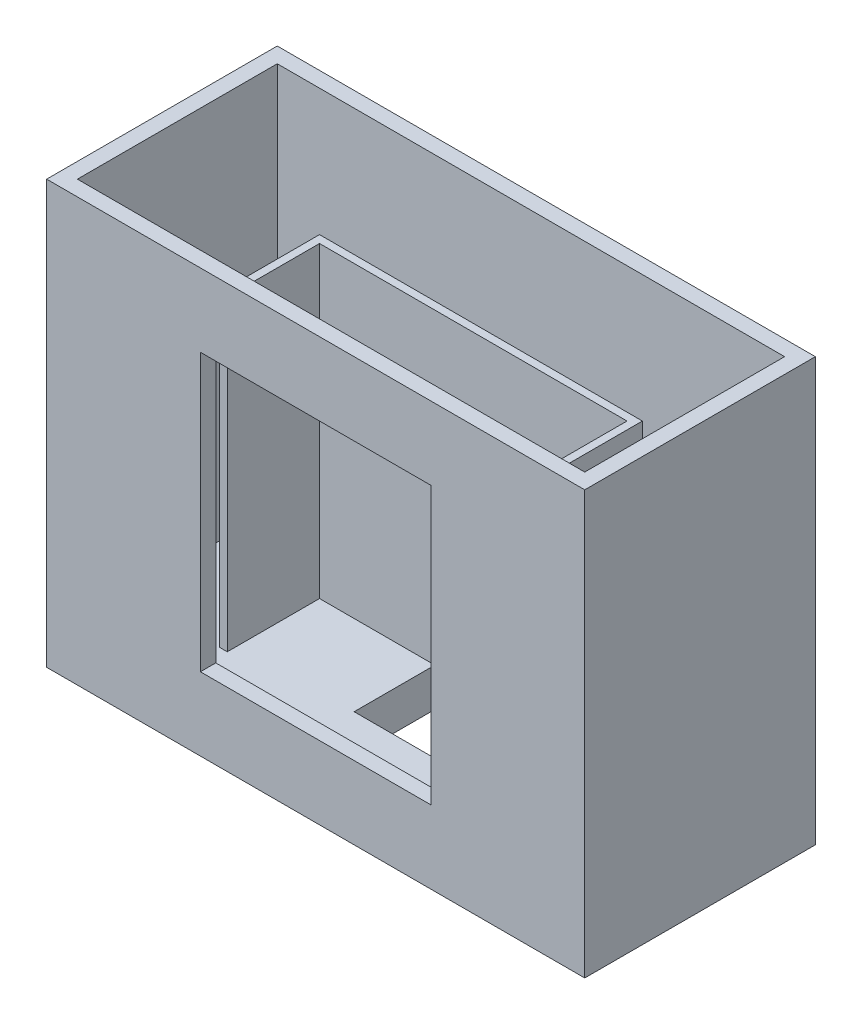
SolidWorks part; units mm, degrees
ref_plane "Front Plane" through (0, 0, 0) normal (0, 0, 1) x (1, 0, 0)
ref_plane "Top Plane" through (0, 0, 0) normal (0, 1, 0) x (1, 0, 0)
ref_plane "Right Plane" through (0, 0, 0) normal (1, 0, 0) x (0, 0, -1)
sketch "Sketch1" plane through (0, 0, 0) normal (0, 1, 0) x (1, 0, 0)
  line L1 (-35, 15) -> (35, 15)
  line L2 (-35, 15) -> (-35, -15)
  line L3 (-35, -15) -> (35, -15)
  line L4 (35, 15) -> (35, -15)
  line L5 (-35, 15) -> (35, -15) construction
  line L6 (-35, -15) -> (35, 15) construction
  point P0 (0, 0)
  dimension "D1" = 30
  dimension "D2" = 70
extrude "Boss-Extrude1" add sketch "Sketch1" along normal blind 5
sketch "Sketch2" plane through (0, 5, 0) normal (0, 1, 0) x (1, 0, 0)
  line L0 (35, -15) -> (35, 15) construction
  line L1 (-35, -15) -> (35, -15)
  line L2 (-35, -15) -> (-35, -13)
  line L3 (-35, -13) -> (35, -13)
  line L4 (35, -15) -> (35, -13)
  line L19 (-35, 15) -> (35, 15)
  line L20 (-35, 15) -> (-35, 13)
  line L21 (-35, 13) -> (35, 13)
  line L22 (35, 15) -> (35, 13)
  dimension "D1" = 2
  dimension "D2" = 2
extrude "Boss-Extrude2" add sketch "Sketch2" along normal blind 50
sketch "Sketch3" plane through (0, 5, 0) normal (0, 1, 0) x (1, 0, 0)
  line L0 (35, -13) -> (-35, -13) construction
  line L1 (-35, 13) -> (-33, 13)
  line L2 (-35, 13) -> (-35, -13)
  line L3 (-35, -13) -> (-33, -13)
  line L4 (-33, 13) -> (-33, -13)
  line L5 (35, -13) -> (-35, -13) construction
  line L6 (35, 13) -> (33, 13)
  line L7 (35, 13) -> (35, -13)
  line L8 (35, -13) -> (33, -13)
  line L9 (33, 13) -> (33, -13)
  dimension "D1" = 2
  dimension "D2" = 2
extrude "Boss-Extrude3" add sketch "Sketch3" along normal blind 50
sketch "Sketch4" plane through (0, 5, 0) normal (0, 1, 0) x (1, 0, 0)
  line L1 (-20, -5.5) -> (20, -5.5)
  line L2 (-20, -5.5) -> (-20, 5.5)
  line L3 (-20, 5.5) -> (20, 5.5)
  line L4 (20, -5.5) -> (20, 5.5)
  line L5 (-20, -5.5) -> (20, 5.5) construction
  line L6 (-20, 5.5) -> (20, -5.5) construction
  line L7 (-21, -6.5) -> (21, -6.5)
  line L8 (-21, -6.5) -> (-21, 6.5)
  line L9 (-21, 6.5) -> (21, 6.5)
  line L10 (21, -6.5) -> (21, 6.5)
  line L11 (-21, -6.5) -> (21, 6.5) construction
  line L12 (-21, 6.5) -> (21, -6.5) construction
  point P0 (0, 0)
  point P6 (0, 0)
  dimension "D1" = 40
  dimension "D2" = 11
  dimension "D3" = 13
  dimension "D4" = 42
extrude "Boss-Extrude4" add sketch "Sketch4" along normal blind 40
sketch "Sketch6" plane through (0, 0, 6.5) normal (0, 0, 1) x (1, 0, 0)
  line L5 (-21, 45) -> (21, 45) construction
  line L8 (-21, 5) -> (21, 5) construction
  line L14 (-20, 45) -> (20, 45)
  line L15 (-20, 45) -> (-20, 5)
  line L16 (-20, 5) -> (20, 5)
  line L17 (20, 45) -> (20, 5)
extrude "Cut-Extrude1" cut sketch "Sketch6" against normal blind 2
sketch "Sketch7" plane through (0, 0, 15) normal (0, 0, 1) x (1, 0, 0)
  line L0 (-35, 27.5) -> (35, 27.5)
  line L1 (-35, 55) -> (-35, 0) construction
  line L2 (35, 55) -> (35, 0) construction
  line L3 (0, 0) -> (0, 55)
  line L4 (-35, 55) -> (35, 55) construction
  line L6 (-15, 9.5) -> (15, 9.5)
  line L7 (-15, 9.5) -> (-15, 45.5)
  line L8 (-15, 45.5) -> (15, 45.5)
  line L9 (15, 9.5) -> (15, 45.5)
  line L10 (-15, 9.5) -> (15, 45.5) construction
  line L11 (-15, 45.5) -> (15, 9.5) construction
  point P11 (0, 27.5)
  dimension "D1" = 36
  dimension "D2" = 30
extrude "Cut-Extrude2" cut sketch "Sketch7" against normal blind 5 contours L8 L7 L0 L3 | L0 L9 L8 L3 | L6 L9 L0 L3 | L7 L6 L3 L0
sketch "Sketch8" plane through (0, 0, 0) normal (0, -1, 0) x (1, 0, 0)
  line L1 (-5, -5) -> (5, -5)
  line L2 (-5, -5) -> (-5, 5)
  line L3 (-5, 5) -> (5, 5)
  line L4 (5, -5) -> (5, 5)
  line L5 (-5, -5) -> (5, 5) construction
  line L6 (-5, 5) -> (5, -5) construction
  point P0 (0, 0)
  dimension "D1" = 10
  dimension "D2" = 10
extrude "Cut-Extrude3" cut sketch "Sketch8" against normal blind 5
